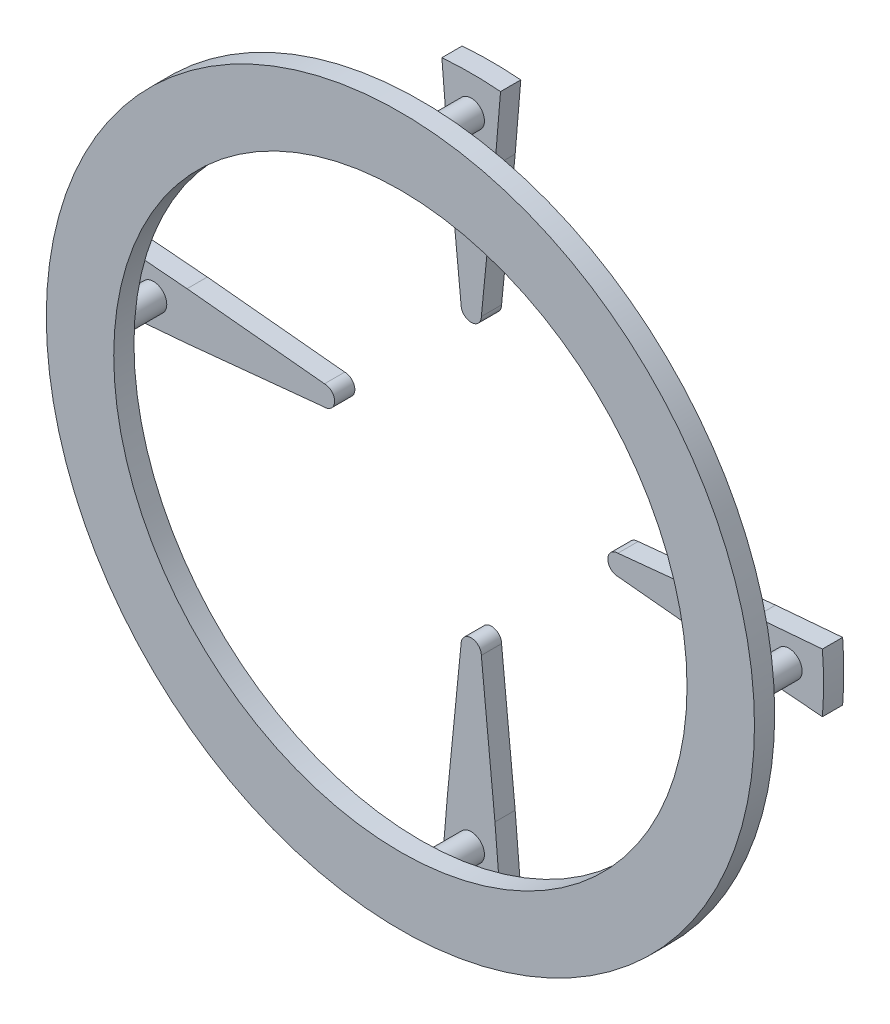
SolidWorks part; units mm, degrees
ref_plane "前基準面" through (0, 0, 0) normal (0, 0, 1) x (1, 0, 0)
ref_plane "上基準面" through (0, 0, 0) normal (0, 1, 0) x (1, 0, 0)
ref_plane "右基準面" through (0, 0, 0) normal (1, 0, 0) x (0, 0, -1)
sketch "草圖1" plane through (0, 0, 0) normal (0, 0, 1) x (1, 0, 0)
  line L0 (-0.03, 0.435) -> (-0.0704, 0.8425)
  line L1 (0, 0.435) -> (0, 0.8542) construction
  line L2 (0.03, 0.435) -> (0.0704, 0.8425)
  line L3 (0.435, 0.03) -> (0.8425, 0.0704)
  line L4 (0.435, -0.03) -> (0.8425, -0.0704)
  line L5 (0.03, -0.435) -> (0.0704, -0.8425)
  line L6 (-0.03, -0.435) -> (-0.0704, -0.8425)
  line L7 (-0.435, -0.03) -> (-0.8425, -0.0704)
  line L8 (-0.435, 0.03) -> (-0.8425, 0.0704)
  line L9 (-0.0704, 0.8425) -> (-0.087, 1.0414)
  line L10 (0.0704, 0.8425) -> (0.087, 1.0414)
  line L11 (0.8425, 0.0704) -> (1.0414, 0.087)
  line L12 (0.8425, -0.0704) -> (1.0414, -0.087)
  line L13 (-0.0704, -0.8425) -> (-0.087, -1.0414)
  line L14 (0.0704, -0.8425) -> (0.087, -1.0414)
  line L15 (-0.8425, 0.0704) -> (-1.0414, 0.087)
  line L16 (-0.8425, -0.0704) -> (-1.0414, -0.087)
  circle A0 centre (0, 0) radius 0.405
  arc A2 (-0.03, 0.435) -> (0.03, 0.435) centre (0, 0.435) ccw
  arc A4 (0.435, 0.03) -> (0.435, -0.03) centre (0.435, 0) ccw
  arc A6 (0.03, -0.435) -> (-0.03, -0.435) centre (0, -0.435) ccw
  arc A8 (-0.435, -0.03) -> (-0.435, 0.03) centre (-0.435, 0) ccw
  arc A9 (0.0704, 0.8425) -> (-0.0704, 0.8425) centre (0, 0) ccw
  arc A10 (0.087, 1.0414) -> (-0.087, 1.0414) centre (0, 0) ccw
  arc A11 (-1.0414, 0.087) -> (-1.0414, -0.087) centre (0, 0) ccw
  arc A12 (-0.8425, 0.0704) -> (-0.8425, -0.0704) centre (0, 0) ccw
  arc A13 (-0.0704, -0.8425) -> (0.0704, -0.8425) centre (0, 0) ccw
  arc A14 (-0.087, -1.0414) -> (0.087, -1.0414) centre (0, 0) ccw
  arc A15 (1.0414, -0.087) -> (1.0414, 0.087) centre (0, 0) ccw
  arc A16 (0.8425, -0.0704) -> (0.8425, 0.0704) centre (0, 0) ccw
  point P27 (0, 0)
  dimension "D1" = 5.66
  dimension "D2" = 4
extrude "填料-伸長1" add sketch "草圖1" along normal blind 0.06
sketch "草圖2" plane through (0, 0, 0.06) normal (0, 0, 1) x (1, 0, 0)
  line L0 (0.9419, 0.0787) -> (0.9419, -0.1053) construction
  line L1 (0.8425, 0.0704) -> (1.0414, 0.087) construction
  line L2 (1.05, 0) -> (0.6277, 0) construction
  line L3 (0.8425, -0.0704) -> (1.0414, -0.087) construction
  circle A0 centre (0, 0) radius 0.85
  circle A1 centre (0, 0) radius 1.05
  circle A3 centre (0.9419, 0) radius 0.07
  circle A4 centre (0, -0.9419) radius 0.07
  circle A5 centre (-0.9419, 0) radius 0.07
  circle A6 centre (0, 0.9419) radius 0.07
  circle A7 centre (0.9419, 0) radius 0.01
  circle A8 centre (0, -0.9419) radius 0.01
  circle A9 centre (-0.9419, 0) radius 0.01
  circle A10 centre (0, 0.9419) radius 0.01
  point P10 (0.9419, 0)
  point P11 (0.847, 0.0708)
  point P12 (0.847, -0.0708)
  point P26 (0, 0)
  point P34 (0, 0)
  dimension "D1" = 4
  dimension "D2" = 4
extrude "填料-伸長2" add sketch "草圖2" along normal blind 0.15 contours A7 | A10 | A9 | A8
sketch "草圖3" plane through (0, 0, 0.21) normal (0, 0, 1) x (1, 0, 0)
  circle A0 centre (0, 0) radius 0.85
  circle A1 centre (0, 0) radius 1.05
extrude "填料-伸長3" add sketch "草圖3" along normal blind 0.06
sketch "草圖6" plane through (0, 0, 0.06) normal (0, 0, 1) x (1, 0, 0)
  circle A0 centre (0.9419, 0) radius 0.02
  circle A1 centre (0.9419, 0) radius 0.0393
  circle A2 centre (0, -0.9419) radius 0.0393
  circle A3 centre (0, -0.9419) radius 0.02
  circle A4 centre (-0.9419, 0) radius 0.0393
  circle A5 centre (-0.9419, 0) radius 0.02
  circle A6 centre (0, 0.9419) radius 0.0393
  circle A7 centre (0, 0.9419) radius 0.02
  point P16 (0, 0)
  dimension "D1" = 4
extrude "填料-伸長4" add sketch "草圖6" along normal blind 0.15
